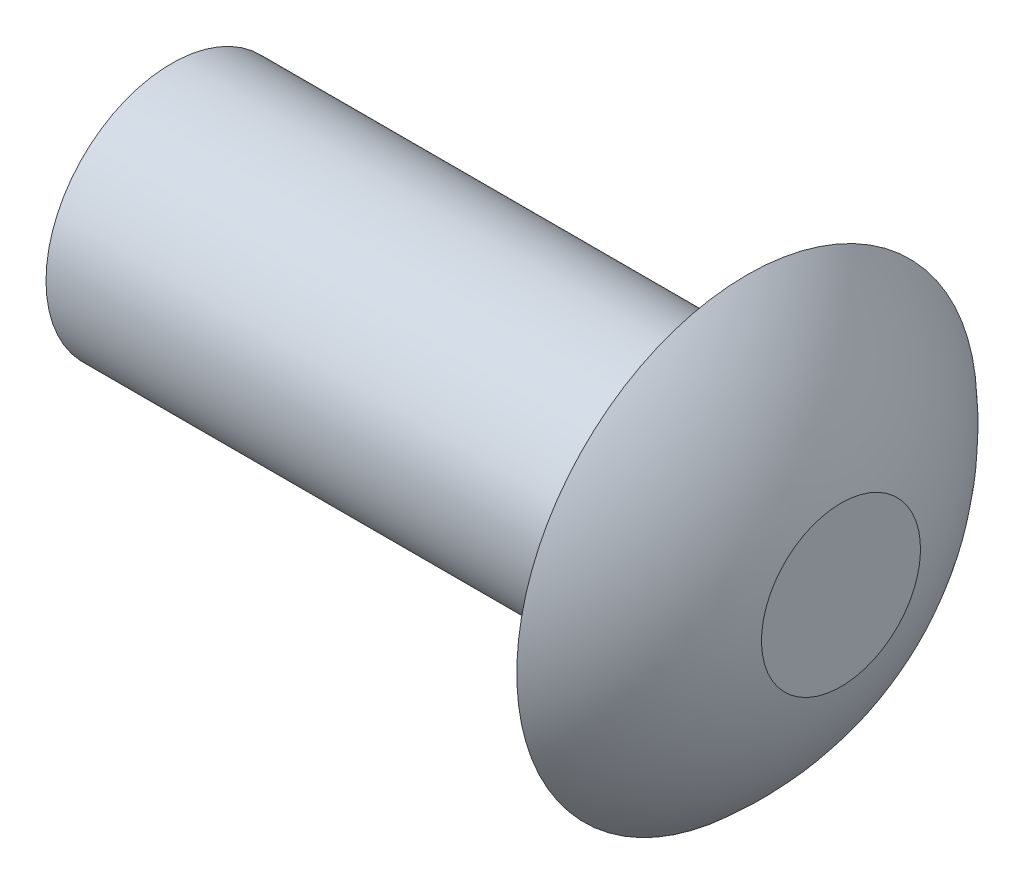
SolidWorks part; units mm, degrees
material "Stainless Steel (ferritic)"
ref_plane "Front Plane" through (0, 0, 0) normal (0, 0, 1) x (1, 0, 0)
ref_plane "Top Plane" through (0, 0, 0) normal (0, 1, 0) x (1, 0, 0)
ref_plane "Right Plane" through (0, 0, 0) normal (1, 0, 0) x (0, 0, -1)
sketch "Sketch1" plane through (0, 0, 0) normal (0, 0, 1) x (1, 0, 0)
  line L0 (-6.8758, 1.5) -> (0, 1.5)
  line L1 (0, 1.5) -> (0, 49000) construction
  line L2 (-6.8758, 0) -> (1.1242, 0)
  line L3 (-6.8758, 0) -> (-6.8758, 1.5)
  line L4 (-1000, 0) -> (49000, 0) construction
  line L5 (0, -1000) -> (0, 0.95) construction
  line L7 (0, 2.75) -> (0, 1.5)
  line L9 (1.1242, 0) -> (1.1242, 0.95)
  arc A0 (0, 2.75) -> (1.1242, 0.95) centre (-2.4, 0) cw
  point P11 (1.25, 0)
  dimension "D1" = 1.9
  dimension "D2" = 8
  dimension "D3" = 90
  dimension "D4" = 3
  dimension "D5" = 5.5
  dimension "D6" = 1.25
revolve "Revolve1" add sketch "Sketch1" angle 360 about L4
